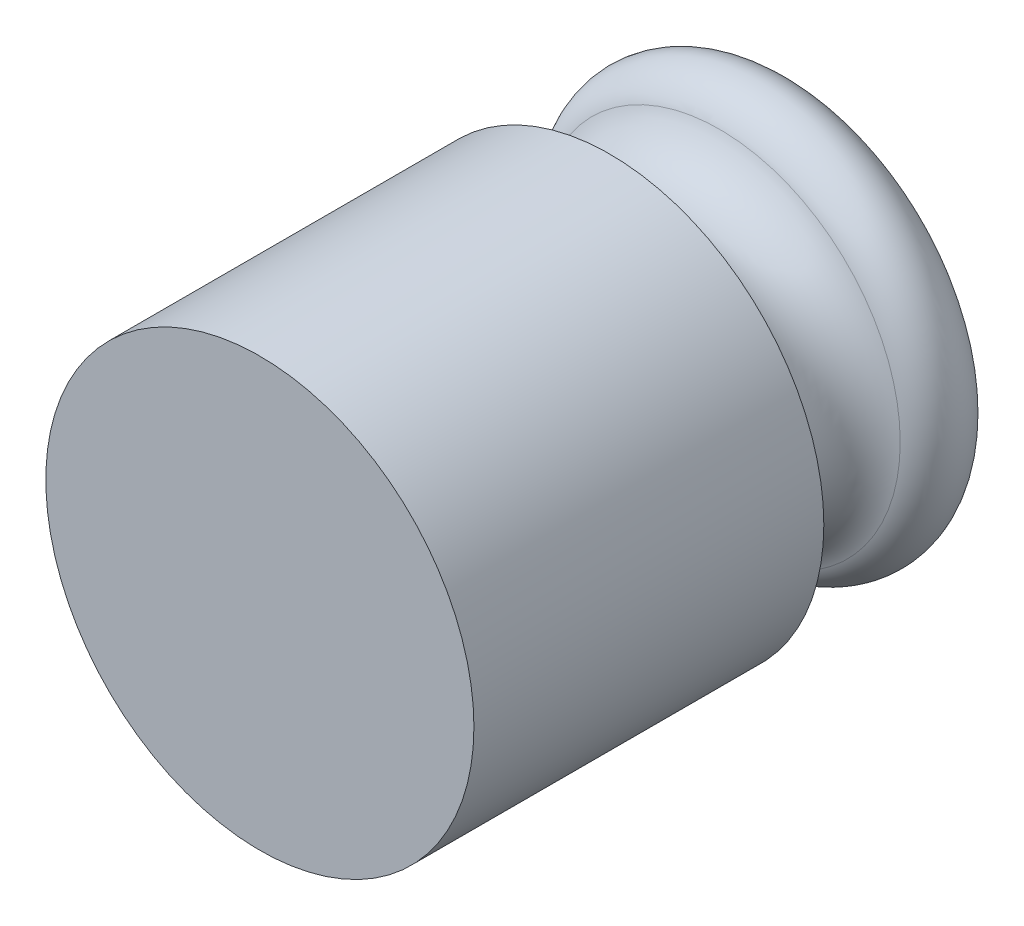
SolidWorks part; units mm, degrees
ref_plane "Front Plane" through (0, 0, 0) normal (0, 0, 1) x (1, 0, 0)
ref_plane "Top Plane" through (0, 0, 0) normal (0, 1, 0) x (1, 0, 0)
ref_plane "Right Plane" through (0, 0, 0) normal (1, 0, 0) x (0, 0, -1)
sketch "Sketch1" plane through (0, 0, 0) normal (0, 0, 1) x (1, 0, 0)
  circle A0 centre (0, 0) radius 15.6
  dimension "D1" = 31.2
extrude "Boss-Extrude1" add sketch "Sketch1" along normal mid plane 25.5
sketch "Sketch2" plane through (0, 0, 0) normal (1, 0, 0) x (0, 0, -1)
  line L0 (12.75, 0) -> (20.75, 0)
  line L1 (12.75, -15.6) -> (12.75, 15.6) construction
  line L2 (26.25, 12.1574) -> (26.25, 0)
  line L3 (26.25, 0) -> (20.75, 0)
  line L4 (12.75, 14.6347) -> (12.75, 0)
  arc A0 (12.75, 14.6347) -> (20.75, 13.1667) centre (16.8847, 14.6347) ccw
  arc A1 (20.75, 13.1667) -> (26.25, 12.1574) centre (23.4074, 12.1574) cw
  point P13 (16.8847, 10.5)
  point P18 (23.4074, 15)
  dimension "D1" = 8
  dimension "D2" = 5.5
  dimension "D3" = 15
  dimension "D4" = 10.5
revolve "Revolve1" add sketch "Sketch2" angle 360 about L0
ref_plane "Plane1" through (0, 0, -6.75) normal (0, 0, -1) x (-1, 0, 0)
